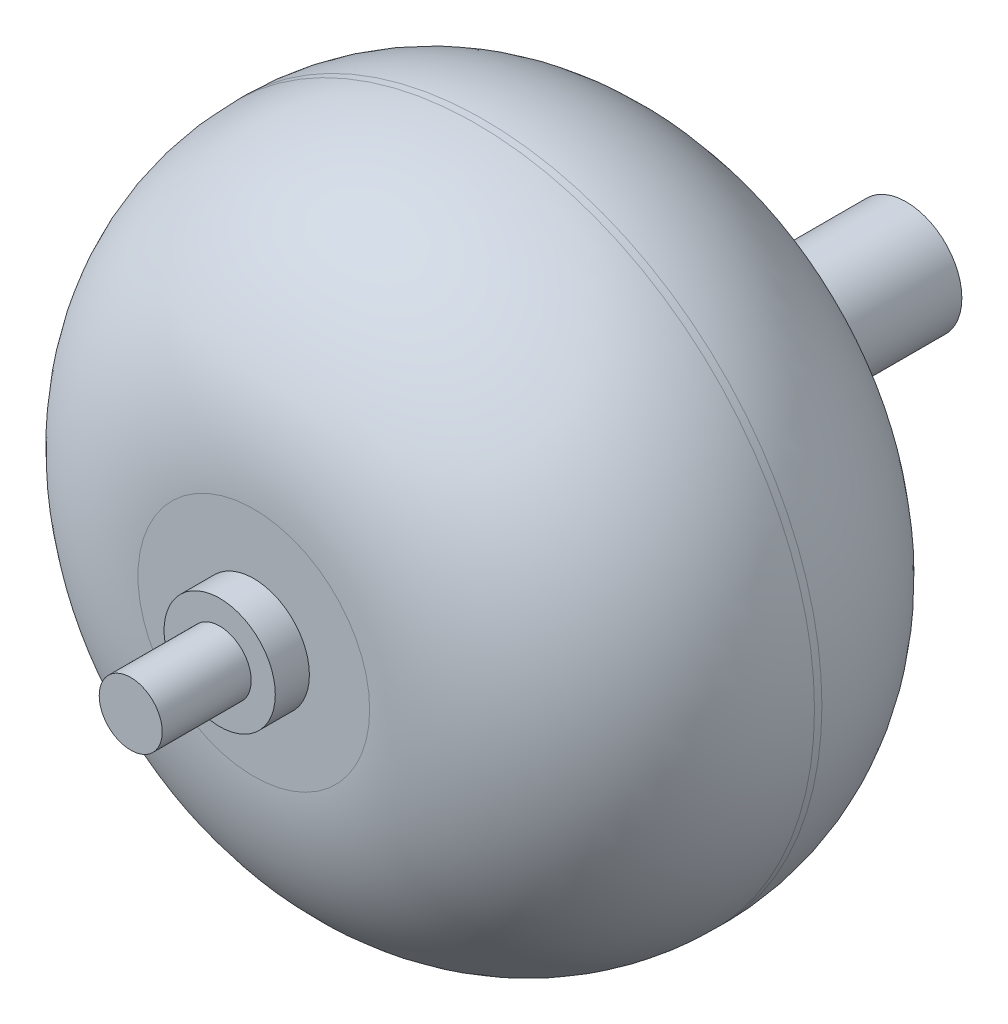
SolidWorks part; units mm, degrees
ref_plane "Front Plane" through (0, 0, 0) normal (0, 0, 1) x (1, 0, 0)
ref_plane "Top Plane" through (0, 0, 0) normal (0, 1, 0) x (1, 0, 0)
ref_plane "Right Plane" through (0, 0, 0) normal (1, 0, 0) x (0, 0, -1)
sketch "Sketch1" plane through (0, 0, 0) normal (0, 0, 1) x (1, 0, 0)
  circle A0 centre (0, 0) radius 9.125
extrude "Boss-Extrude1" add sketch "Sketch1" along normal blind 12.2
sketch "Sketch2" plane through (0, 0, 0) normal (0, 0, -1) x (-1, 0, 0)
  circle A0 centre (0, 0) radius 1.5
extrude "Boss-Extrude2" add sketch "Sketch2" along normal blind 5.4
sketch "Sketch4" plane through (0, 0, 12.2) normal (0, 0, 1) x (1, 0, 0)
  circle A0 centre (0, 0) radius 1.5
extrude "Boss-Extrude3" add sketch "Sketch4" along normal blind 0.92
sketch "Sketch5" plane through (0, 0, 12.2) normal (0, 0, 1) x (1, 0, 0)
  circle A0 centre (0, 0) radius 0.85
extrude "Boss-Extrude4" add sketch "Sketch5" along normal blind 3.32
fillet "Fillet1" radius 6 2 edges at (9.125, 0, 12.2) (9.125, 0, 0)
